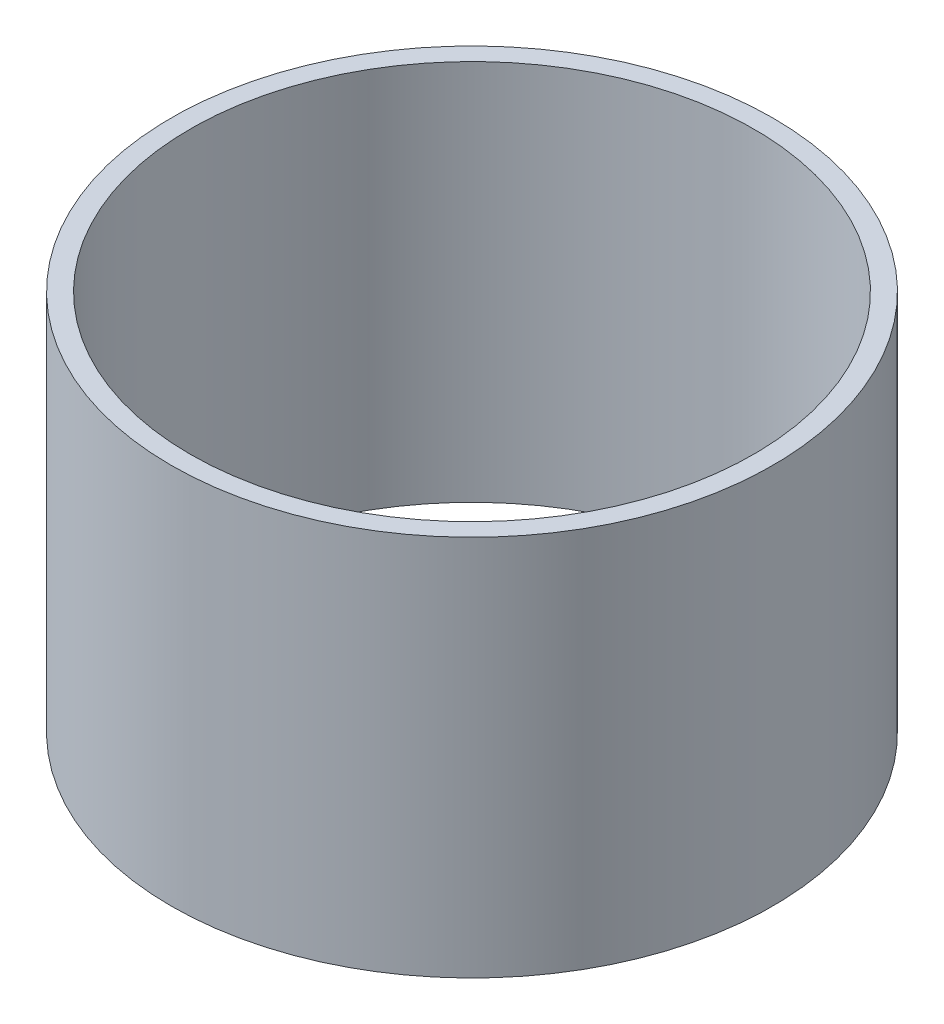
SolidWorks part; units mm, degrees
ref_plane "Front Plane" through (0, 0, 0) normal (0, 0, 1) x (1, 0, 0)
ref_plane "Top Plane" through (0, 0, 0) normal (0, 1, 0) x (1, 0, 0)
ref_plane "Right Plane" through (0, 0, 0) normal (1, 0, 0) x (0, 0, -1)
sketch "Sketch1" plane through (0, 0, 0) normal (0, 1, 0) x (1, 0, 0)
  circle A0 centre (0, 0) radius 40.04
  circle A1 centre (0, 0) radius 37.5
  dimension "D1" = 75
  dimension "D2" = 2.54
extrude "Boss-Extrude1" add sketch "Sketch1" along normal blind 50.8
